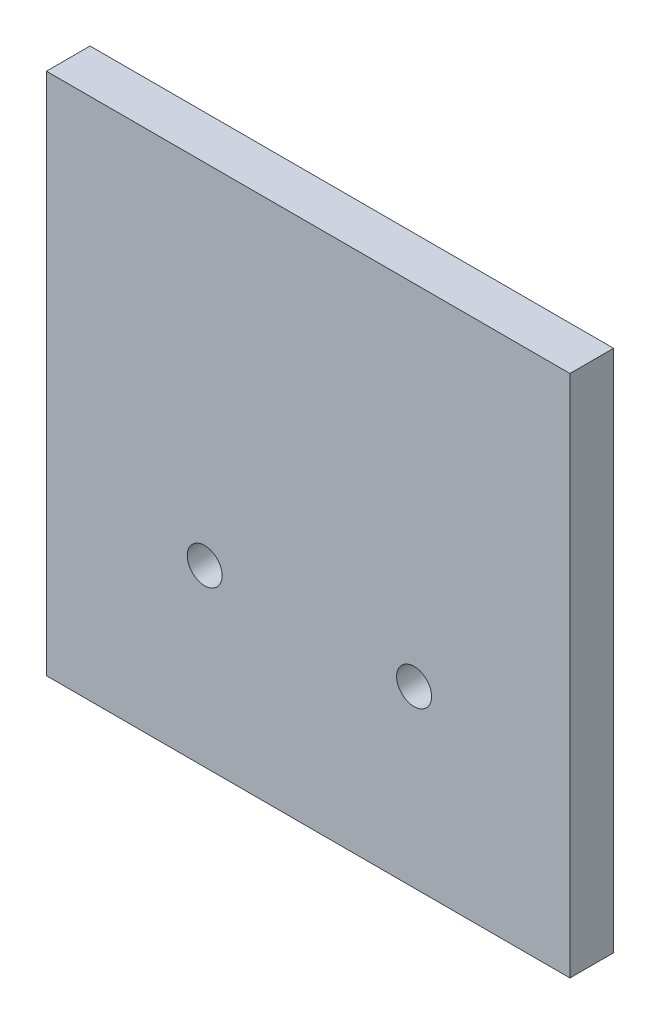
SolidWorks part; units mm, degrees
ref_plane "Alzado" through (0, 0, 0) normal (0, 0, 1) x (1, 0, 0)
ref_plane "Planta" through (0, 0, 0) normal (0, 1, 0) x (1, 0, 0)
ref_plane "Vista lateral" through (0, 0, 0) normal (1, 0, 0) x (0, 0, -1)
sketch "Croquis1" plane through (0, 0, 0) normal (0, 0, 1) x (1, 0, 0)
  line L0 (-150.6885, 104.9107) -> (-150.6885, -195.0893)
  line L1 (-150.6885, -195.0893) -> (149.3115, -195.0893)
  line L2 (149.3115, -195.0893) -> (149.3115, 104.9107)
  line L3 (149.3115, 104.9107) -> (-150.6885, 104.9107)
  dimension "D1" = 300
  dimension "D2" = 300
extrude "Saliente-Extruir1" add sketch "Croquis1" along normal blind 25
sketch "Croquis2" plane through (0, 0, 25) normal (0, 0, 1) x (1, 0, 0)
  line L1 (-150.6885, -195.0893) -> (149.3115, -195.0893) construction
  line L2 (-60, -95.0893) -> (60, -95.0893) construction
  circle A0 centre (-60, -95.0893) radius 10
  circle A1 centre (60, -95.0893) radius 10
  point P4 (0, -95.0893)
  dimension "D1" = 20
  dimension "D3" = 120
  dimension "D4" = 100
extrude "Cortar-Extruir1" cut sketch "Croquis2" against normal blind 25
